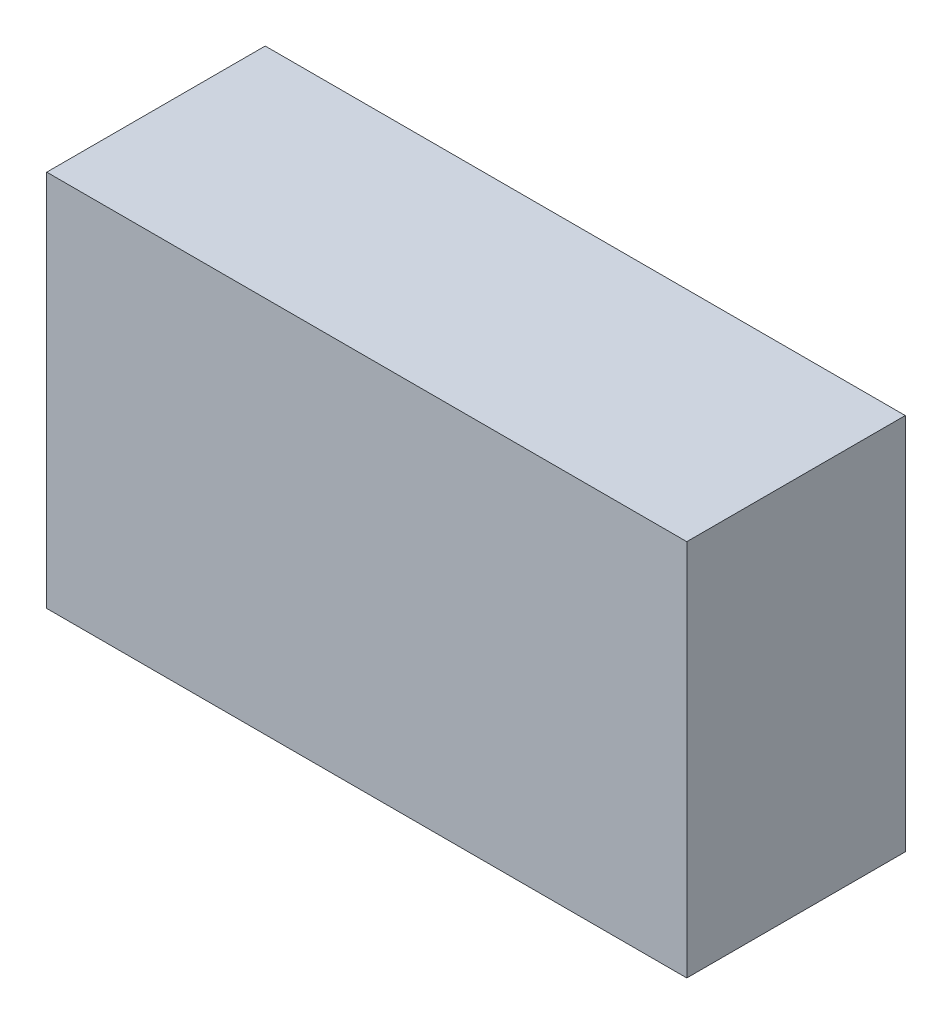
SolidWorks part; units mm, degrees
ref_plane "Front Plane" through (0, 0, 0) normal (0, 0, 1) x (1, 0, 0)
ref_plane "Top Plane" through (0, 0, 0) normal (0, 1, 0) x (1, 0, 0)
ref_plane "Right Plane" through (0, 0, 0) normal (1, 0, 0) x (0, 0, -1)
sketch "Sketch1" plane through (0, 0, 0) normal (0, 0, 1) x (1, 0, 0)
  line L0 (-16.9755, 30.39) -> (4.6645, 30.39) construction
  line L1 (-16.7755, 30.19) -> (4.4645, 30.19)
  line L2 (-16.7755, 30.19) -> (-16.7755, 17.65)
  line L3 (-16.7755, 17.65) -> (4.4645, 17.65)
  line L4 (4.4645, 30.19) -> (4.4645, 17.65)
  line L5 (4.6645, 30.39) -> (4.6645, 17.45) construction
  line L6 (4.6645, 17.45) -> (-16.9755, 17.45) construction
  line L7 (-16.9755, 30.39) -> (-16.9755, 17.45) construction
  point P10 (-16.9755, 23.92)
  dimension "D1" = 0.2
  dimension "D2" = 0.2
  dimension "D3" = 0.2
  dimension "D4" = 0.2
extrude "Boss-Extrude1" add sketch "Sketch1" along normal blind 7.25
shell "Shell1" thickness 0.5
